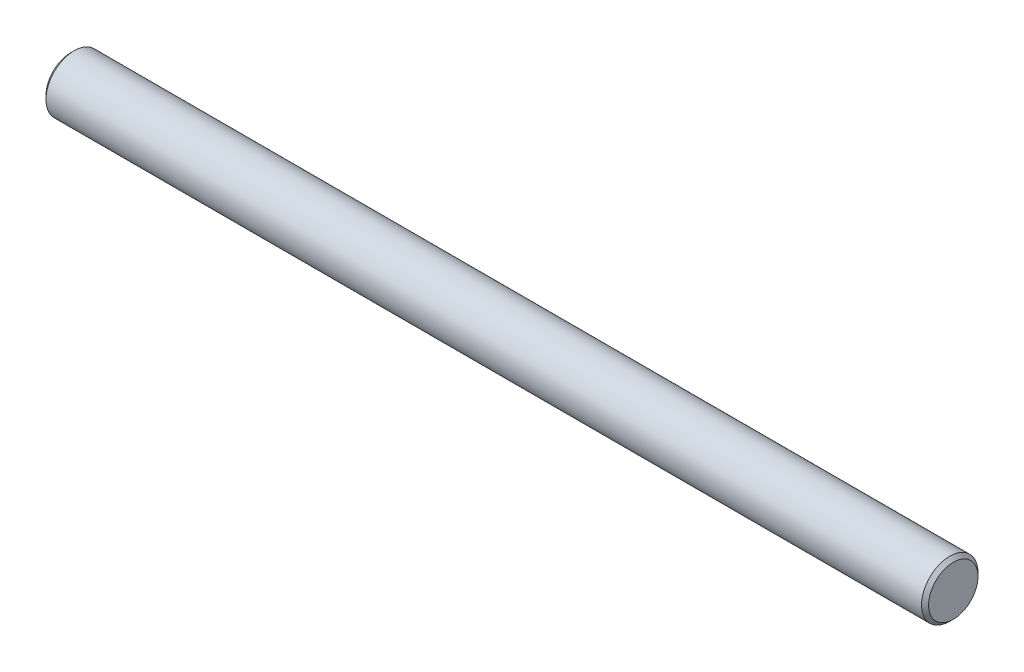
SolidWorks part; units mm, degrees
ref_plane "Front Plane" through (0, 0, 0) normal (0, 0, 1) x (1, 0, 0)
ref_plane "Top Plane" through (0, 0, 0) normal (0, 1, 0) x (1, 0, 0)
ref_plane "Right Plane" through (0, 0, 0) normal (1, 0, 0) x (0, 0, -1)
sketch "Sketch1" plane through (0, 0, 0) normal (1, 0, 0) x (0, 0, -1)
  circle A0 centre (0, 0) radius 4
  dimension "D1" = 8
extrude "Boss-Extrude1" add sketch "Sketch1" along normal blind 125
chamfer "Chamfer1" distance 0.5 angle 45 2 edges at (125, 0, -4) (0, 0, -4)
